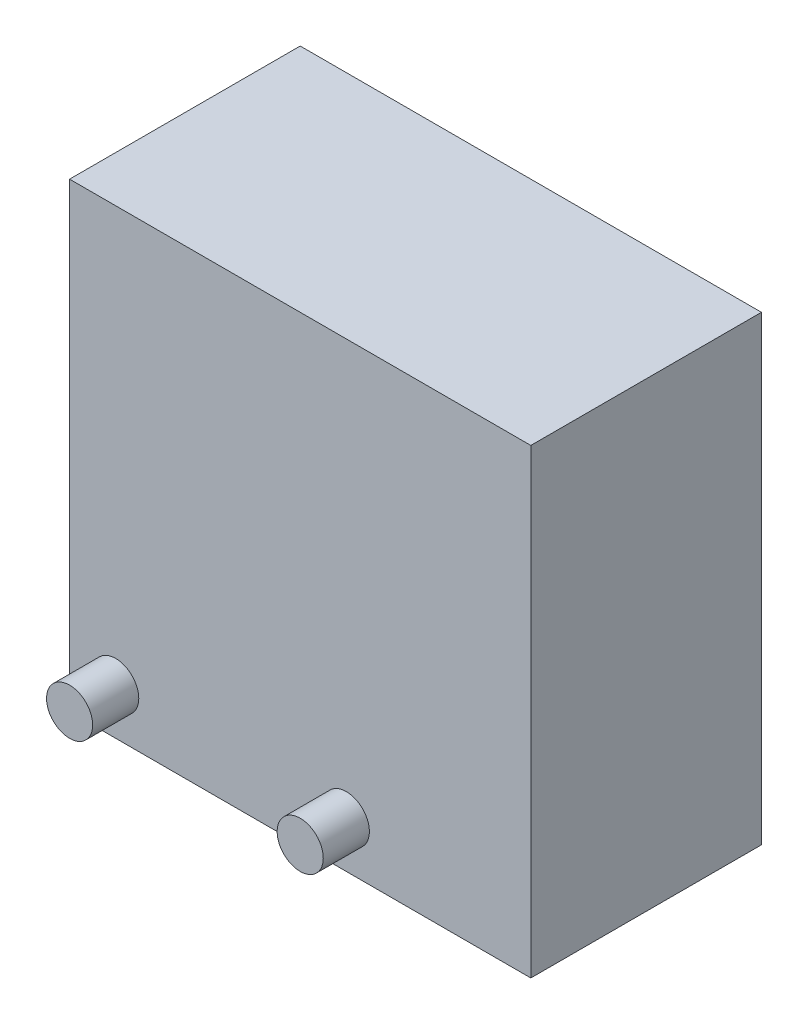
SolidWorks part; units mm, degrees
ref_plane "前视基准面" through (0, 0, 0) normal (0, 0, 1) x (1, 0, 0)
ref_plane "上视基准面" through (0, 0, 0) normal (0, 1, 0) x (1, 0, 0)
ref_plane "右视基准面" through (0, 0, 0) normal (1, 0, 0) x (0, 0, -1)
other "Configuration Table"
sketch "草图1" plane through (0, 0, 0) normal (0, 0, 1) x (1, 0, 0)
  line L1 (0, 0) -> (20, 0)
  line L2 (0, 0) -> (0, 20)
  line L3 (0, 20) -> (20, 20)
  line L4 (20, 0) -> (20, 20)
extrude "BaseBox" add sketch "草图1" along normal blind 10
sketch "草图2" plane through (0, 0, 10) normal (0, 0, 1) x (1, 0, 0)
  circle A0 centre (2, 2) radius 1
extrude "BossSeed" add sketch "草图2" along normal blind 2
pattern_linear "LinearPattern" count 2 spacing 10 along (1, 0, 0) count 3 spacing 15 along (0, -1, 0) of "BossSeed"
